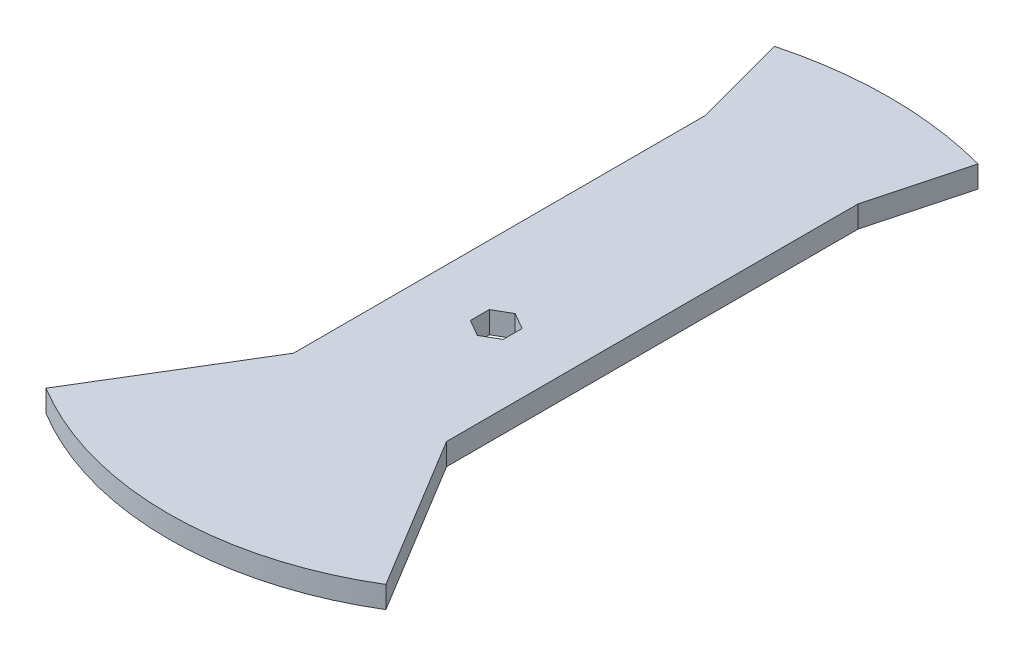
SolidWorks part; units mm, degrees
ref_plane "Front Plane" through (0, 0, 0) normal (0, 0, 1) x (1, 0, 0)
ref_plane "Top Plane" through (0, 0, 0) normal (0, 1, 0) x (1, 0, 0)
ref_plane "Right Plane" through (0, 0, 0) normal (1, 0, 0) x (0, 0, -1)
sketch "Sketch1" plane through (0, 0, 0) normal (0, 1, 0) x (1, 0, 0)
  line L0 (0, 114.3) -> (0, -114.3) construction
  line L1 (-5.7523, 21.4677) -> (-29.583, 110.4053) construction
  line L2 (-11.5221, -19.0051) -> (-49.3802, -81.4503) construction
  line L3 (11.5221, -19.0051) -> (49.3802, -81.4503) construction
  line L4 (5.7523, 21.4677) -> (29.583, 110.4053) construction
  line L5 (-22.225, 82.9448) -> (-22.225, -36.6591)
  line L6 (22.225, 82.9448) -> (22.225, -36.6591)
  line L7 (-29.583, 110.4053) -> (-22.225, 82.9448)
  line L8 (22.225, 82.9448) -> (29.583, 110.4053)
  line L9 (-22.225, -36.6591) -> (-49.3802, -81.4503)
  line L10 (22.225, -36.6591) -> (49.3802, -81.4503)
  circle A0 centre (0, 0) radius 22.225 construction
  circle A1 centre (0, 0) radius 114.3 construction
  circle A2 centre (0, 0) radius 95.25 construction
  arc A3 (-49.3802, -81.4503) -> (49.3802, -81.4503) centre (0, 0) ccw
  arc A4 (-29.583, 110.4053) -> (29.583, 110.4053) centre (0, 0) cw
  dimension "D1" = 44.45
  dimension "D2" = 30
  dimension "D3" = 228.6
  dimension "D4" = 190.5
  dimension "D5" = 62.454
extrude "Boss-Extrude1" add sketch "Sketch1" along normal mid plane 6.35
sketch "Sketch2" plane through (0, 3.175, 0) normal (0, 1, 0) x (1, 0, 0)
  line L1 (4.7625, -2.7496) -> (4.7625, 2.7496)
  line L2 (4.7625, 2.7496) -> (0, 5.4993)
  line L3 (0, 5.4993) -> (-4.7625, 2.7496)
  line L4 (-4.7625, 2.7496) -> (-4.7625, -2.7496)
  line L5 (-4.7625, -2.7496) -> (0, -5.4993)
  line L6 (0, -5.4993) -> (4.7625, -2.7496)
  circle A0 centre (0, 0) radius 4.7625 construction
  dimension "D1" = 9.525
extrude "Cut-Extrude1" cut sketch "Sketch2" against normal up to next
